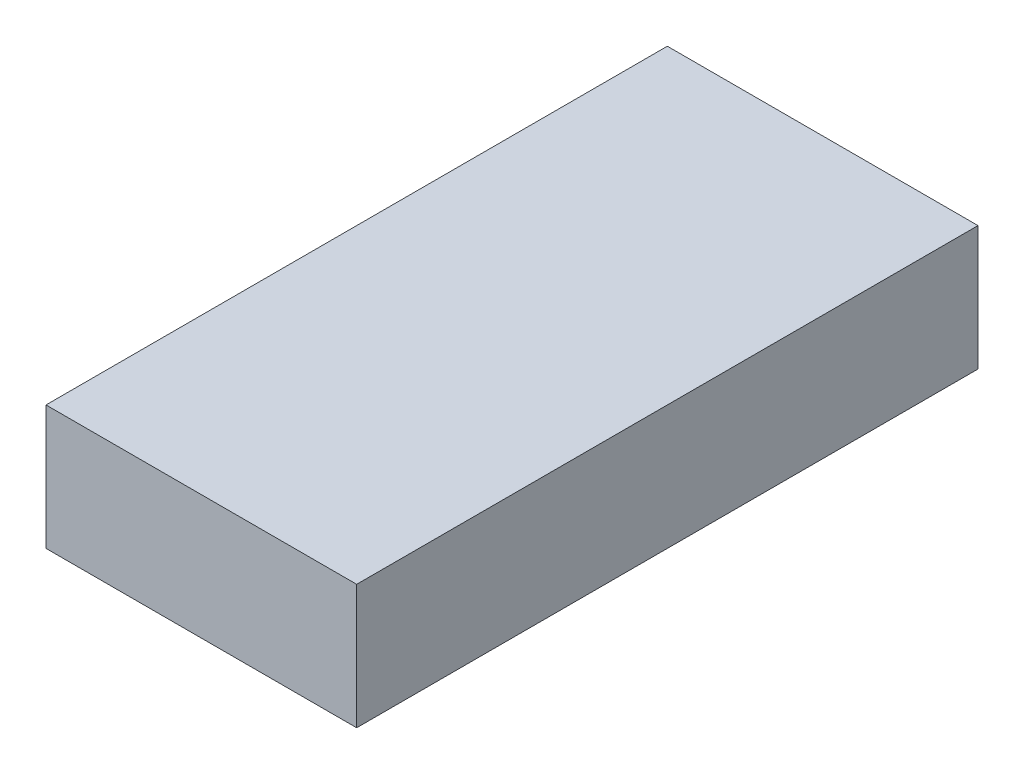
SolidWorks part; units mm, degrees
ref_plane "Front Plane" through (0, 0, 0) normal (0, 0, 1) x (1, 0, 0)
ref_plane "Top Plane" through (0, 0, 0) normal (0, 1, 0) x (1, 0, 0)
ref_plane "Right Plane" through (0, 0, 0) normal (1, 0, 0) x (0, 0, -1)
sketch "Sketch1" plane through (0, 0, 0) normal (0, 1, 0) x (1, 0, 0)
  line L1 (-25, -50) -> (25, -50)
  line L2 (-25, -50) -> (-25, 50)
  line L3 (-25, 50) -> (25, 50)
  line L4 (25, -50) -> (25, 50)
  line L5 (-25, -50) -> (25, 50) construction
  line L6 (-25, 50) -> (25, -50) construction
  point P0 (0, 0)
  dimension "D1" = 50
  dimension "D2" = 100
extrude "Boss-Extrude1" add sketch "Sketch1" along normal blind 20
equation "\"A\"= 50"
equation "\"b\"= 100"
equation "\"C\"= 100"
